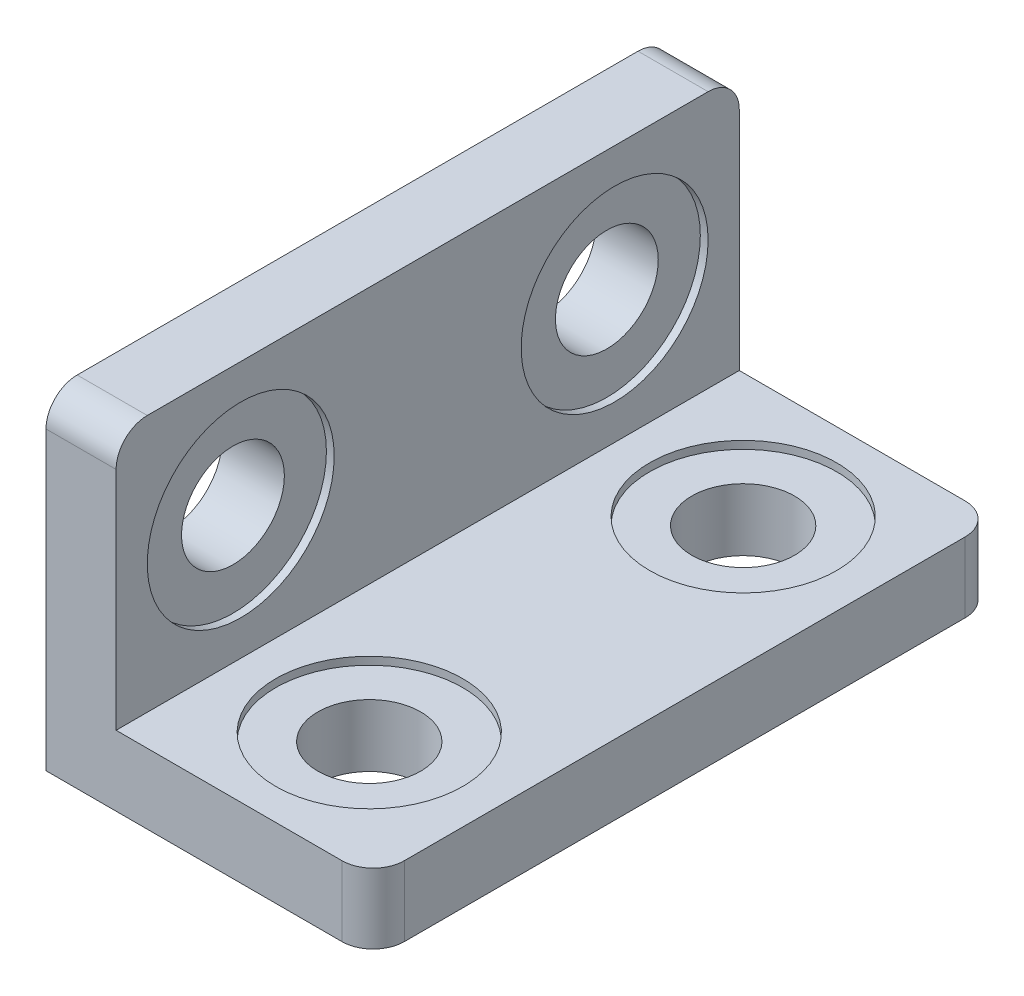
SolidWorks part; units mm, degrees
ref_plane "前视基准面（中心面）" through (0, 0, 0) normal (0, 0, 1) x (1, 0, 0)
ref_plane "上视基准面" through (0, 0, 0) normal (0, 1, 0) x (1, 0, 0)
ref_plane "右视基准面" through (0, 0, 0) normal (1, 0, 0) x (0, 0, -1)
sketch "草图1" plane through (0, 0, 0) normal (0, 0, 1) x (1, 0, 0)
  line L0 (0, 21) -> (0, 0)
  line L1 (0, 0) -> (21, 0)
  line L2 (21, 0) -> (21, 4.5)
  line L3 (21, 4.5) -> (4.5, 4.5)
  line L4 (4.5, 4.5) -> (4.5, 21)
  line L5 (4.5, 21) -> (0, 21)
  dimension "D1" = 21
  dimension "D2" = 4.5
extrude "凸台-拉伸1" add sketch "草图1" along normal mid plane 40
hole_wizard "M6 六角头螺栓的柱形沉头孔1" positions "草图2" profile "草图3" counterbore size "M6" standard "GB" end condition through all
sketch "草图2" plane through (0, 4.5, 0) normal (0, 1, 0) x (1, 0, 0)
  line L0 (12.75, 20) -> (12.75, 12) construction
  line L1 (21, 20) -> (4.5, 20) construction
  line L2 (12.75, 12) -> (12.75, -12) construction
  line L4 (12.75, -12) -> (12.75, -20) construction
  line L5 (21, -20) -> (4.5, -20) construction
  point P0 (12.75, 12)
  point P2 (12.75, -12)
  dimension "D1" = 8
sketch "草图3" plane through (12.75, 4.5, -12) normal (1, 0, 0) x (0, 0, 1)
  line L0 (0, 0) -> (0, 4.5)
  line L1 (0, 4.5) -> (3.3, 4.5)
  line L3 (3.3, 4.5) -> (3.3, 0.5)
  line L4 (3.3, 0.5) -> (6, 0.5)
  line L5 (6, 0.5) -> (6, 0)
  line L7 (6, 0) -> (0, 0)
  line L11 (0, -6.35) -> (0, 107.95) construction
  dimension "通孔孔直径" = 6.6
  dimension "通孔孔深度" = 4.5
  dimension "柱形沉头孔直径" = 12
  dimension "柱形沉头孔深度" = 0.5
hole_wizard "M6 六角头螺栓的柱形沉头孔2" positions "草图4" profile "草图5" counterbore size "M6" standard "GB" end condition through all
sketch "草图4" plane through (4.5, 0, 0) normal (1, 0, 0) x (0, 0, -1)
  line L0 (-20, 12.75) -> (-12, 12.75) construction
  line L1 (-20, 4.5) -> (-20, 21) construction
  line L2 (-12, 12.75) -> (12, 12.75) construction
  line L3 (12, 12.75) -> (20, 12.75) construction
  line L4 (20, 4.5) -> (20, 21) construction
  point P0 (12, 12.75)
  point P2 (-12, 12.75)
  dimension "D1" = 8
sketch "草图5" plane through (4.5, 12.75, -12) normal (0, 1, 0) x (0, 0, -1)
  line L0 (0, 0) -> (0, 4.5)
  line L1 (0, 4.5) -> (3.3, 4.5)
  line L3 (3.3, 4.5) -> (3.3, 0.5)
  line L4 (3.3, 0.5) -> (6, 0.5)
  line L5 (6, 0.5) -> (6, 0)
  line L7 (6, 0) -> (0, 0)
  line L11 (0, -6.35) -> (0, 107.95) construction
  dimension "通孔孔直径" = 6.6
  dimension "通孔孔深度" = 4.5
  dimension "柱形沉头孔直径" = 12
  dimension "柱形沉头孔深度" = 0.5
fillet "圆角1" radius 2 4 edges at (2.25, 21, 20) (21, 2.25, 20) (21, 2.25, -20) (2.25, 21, -20)
